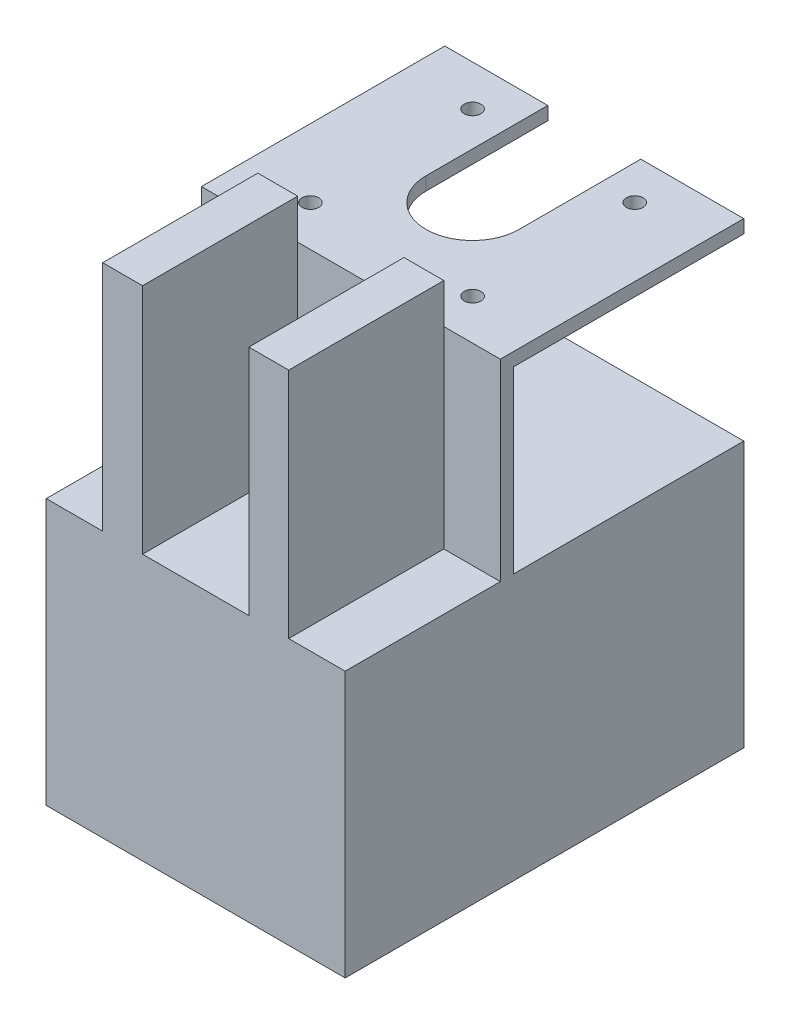
SolidWorks part; units mm, degrees
ref_plane "Front Plane" through (0, 0, 0) normal (0, 0, 1) x (1, 0, 0)
ref_plane "Top Plane" through (0, 0, 0) normal (0, 1, 0) x (1, 0, 0)
ref_plane "Right Plane" through (0, 0, 0) normal (1, 0, 0) x (0, 0, -1)
sketch "Sketch3" plane through (0, 0, 0) normal (0, 1, 0) x (-1, 0, 0)
  line L1 (0, 0) -> (57.15, 0)
  line L2 (0, 0) -> (0, 76.2)
  line L3 (0, 76.2) -> (57.15, 76.2)
  line L4 (57.15, 0) -> (57.15, 76.2)
  point P4 (0, 0)
  dimension "D1" = 76.2
  dimension "D2" = 57.15
extrude "Boss-Extrude2" add sketch "Sketch3" against normal blind 50.8
sketch "Sketch4" plane through (0, -50.8, 0) normal (0, -1, 0) x (1, 0, 0)
  line L1 (-3.81, 72.39) -> (-53.34, 72.39)
  line L2 (-3.81, 72.39) -> (-3.81, 3.81)
  line L3 (-3.81, 3.81) -> (-53.34, 3.81)
  line L4 (-53.34, 72.39) -> (-53.34, 3.81)
  line L8 (-57.15, 76.2) -> (0, 76.2) construction
  line L9 (0, 0) -> (-57.15, 0) construction
  line L10 (0, 76.2) -> (0, 0) construction
  line L11 (-57.15, 0) -> (-57.15, 76.2) construction
  point P4 (-35.3943, 72.7314)
  point P5 (-2.6115, 4.3822)
  dimension "D1" = 3.81
  dimension "D2" = 3.81
  dimension "D3" = 3.81
  dimension "D4" = 3.81
extrude "Cut-Extrude2" cut sketch "Sketch4" against normal blind 44.45
sketch "Sketch5" plane through (-57.15, 0, 0) normal (1, 0, 0) x (0, 0, -1)
  line L1 (-14.478, -46.99) -> (-5.08, -46.99)
  line L2 (-14.478, -46.99) -> (-14.478, -35.56)
  line L3 (-14.478, -35.56) -> (-5.08, -35.56)
  line L4 (-5.08, -46.99) -> (-5.08, -35.56)
  line L6 (0, -50.8) -> (0, 0) construction
  line L7 (0, -50.8) -> (-76.2, -50.8) construction
  point P4 (-71.4281, -45.9494)
  dimension "D1" = 5.08
  dimension "D2" = 3.81
  dimension "D3" = 11.43
  dimension "D4" = 9.398
extrude "Cut-Extrude3" cut sketch "Sketch5" along normal up to next
sketch "Sketch6" plane through (-57.15, 0, 0) normal (-1, 0, 0) x (0, 0, 1)
  line L0 (46.54, 0) -> (46.54, 36.83)
  line L1 (46.54, 36.83) -> (0, 36.83)
  line L2 (0, 36.83) -> (0, 34.29)
  line L3 (0, 34.29) -> (44, 34.29)
  line L4 (44, 34.29) -> (44, 0)
  line L5 (0, 0) -> (76.2, 0) construction
  line L6 (44, 0) -> (46.54, 0)
  line L7 (0, -50.8) -> (0, 0) construction
  dimension "D1" = 44
  dimension "D2" = 34.29
  dimension "D3" = 2.54
  dimension "D4" = 2.54
extrude "Motor Mounting Shape" add sketch "Sketch6" against normal up to surface (57.15 mm away) up to face at (0, -25.4, 38.1)
sketch "Sketch8" plane through (0, 36.83, 0) normal (0, 1, 0) x (1, 0, 0)
  line L0 (-44.075, -38.77) -> (-13.075, -7.77) construction
  line L1 (-13.075, -38.77) -> (-44.075, -7.77) construction
  line L2 (-44.075, -38.77) -> (-44.075, -7.77) construction
  line L3 (-44.075, -7.77) -> (-13.075, -7.77) construction
  line L4 (-28.575, -46.54) -> (-28.575, 0) construction
  line L5 (0, -46.54) -> (-57.15, -46.54) construction
  line L6 (0, 0) -> (-57.15, 0) construction
  line L7 (-37.465, 0) -> (-19.685, 0)
  line L8 (-19.685, 0) -> (-19.685, -23.27)
  line L9 (-37.465, -23.27) -> (-37.465, 0)
  circle A1 centre (-44.075, -7.77) radius 1.6
  circle A2 centre (-13.075, -7.77) radius 1.6
  circle A3 centre (-13.075, -38.77) radius 1.6
  circle A4 centre (-44.075, -38.77) radius 1.6
  arc A6 (-37.465, -23.27) -> (-19.685, -23.27) centre (-28.575, -23.27) ccw
  point P10 (-28.575, -23.27)
  dimension "D2" = 3.2
  dimension "D3" = 8.89
  dimension "D1" = 31
extrude "Motor-Mounting-Holes" cut sketch "Sketch8" against normal up to next
sketch "Sketch7" plane through (0, 0, 0) normal (0, 1, 0) x (1, 0, 0)
  line L0 (-46.355, -76.2) -> (-46.355, -46.54)
  line L1 (-57.15, -76.2) -> (0, -76.2) construction
  line L2 (-46.355, -46.54) -> (-38.735, -46.54)
  line L3 (-38.735, -46.54) -> (-38.735, -76.2)
  line L4 (-38.735, -76.2) -> (-46.355, -76.2)
  line L5 (-18.415, -76.2) -> (-10.795, -76.2)
  line L6 (-10.795, -76.2) -> (-10.795, -46.54)
  line L7 (-10.795, -46.54) -> (-18.415, -46.54)
  line L8 (-18.415, -46.54) -> (-18.415, -76.2)
  line L9 (-46.355, -76.2) -> (-57.15, -76.2) construction
  line L10 (-38.735, -76.2) -> (-18.415, -76.2) construction
  line L11 (-10.795, -76.2) -> (0, -76.2) construction
  line L12 (0, -46.54) -> (-57.15, -46.54) construction
  dimension "D1" = 7.62
  dimension "D2" = 20.32
extrude "Tray Support Mounting Shape" add sketch "Sketch7" along normal blind 44.45
